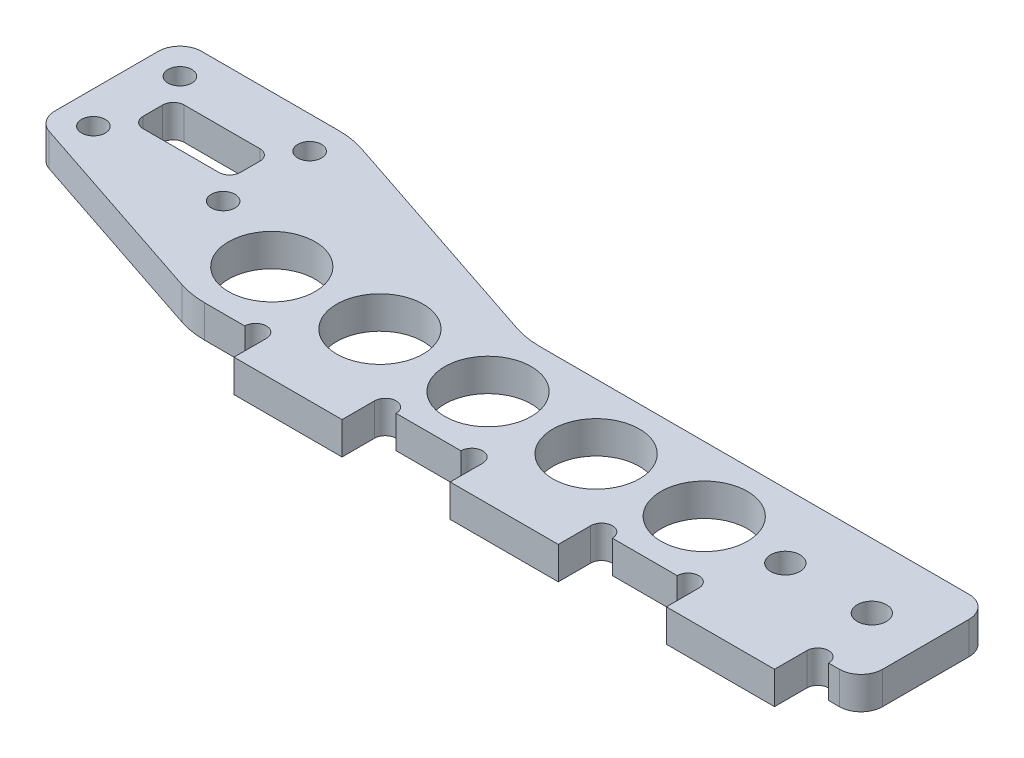
SolidWorks part; units mm, degrees
material "Thornel Mat VMA"
ref_plane "前视基准面" through (0, 0, 0) normal (0, 0, 1) x (1, 0, 0)
ref_plane "上视基准面" through (0, 0, 0) normal (0, 1, 0) x (1, 0, 0)
ref_plane "右视基准面" through (0, 0, 0) normal (1, 0, 0) x (0, 0, -1)
sketch "草图1" plane through (0, 0, 0) normal (0, 1, 0) x (1, 0, 0)
  line L1 (-41.5, -6) -> (41.5, -6)
  line L2 (-41.5, -6) -> (-41.5, 6)
  line L3 (-41.5, 6) -> (41.5, 6)
  line L4 (41.5, -6) -> (41.5, 6)
  line L5 (0, 6) -> (0, -6) construction
  line L6 (-41.5, 0) -> (41.5, 0) construction
  point P0 (0, 0)
  dimension "D4" = 83
  dimension "D5" = 12
extrude "凸台-拉伸1" add sketch "草图1" along normal blind 3
sketch "草图2" plane through (0, 3, 0) normal (0, 1, 0) x (1, 0, 0)
  line L0 (-41.5, 6) -> (-41.5, -6) construction
  line L1 (11.5, -6) -> (11.5, 6) construction
  line L2 (1.5, -6) -> (1.5, 6) construction
  line L3 (16.5, -9) -> (6.5, -9)
  line L4 (-13.5, -6) -> (-3.5, -6)
  line L5 (-13.5, -6) -> (-13.5, -9)
  line L6 (-13.5, -9) -> (-3.5, -9)
  line L7 (-3.5, -6) -> (-3.5, -9)
  line L12 (6.5, -6) -> (6.5, -9)
  line L13 (16.5, -6) -> (6.5, -6)
  line L14 (16.5, -6) -> (16.5, -9)
  line L15 (36.5, -9) -> (26.5, -9)
  line L16 (41.5, 6) -> (-41.5, 6) construction
  line L17 (-41.5, -6) -> (41.5, -6) construction
  line L18 (26.5, -6) -> (26.5, -9)
  line L19 (36.5, -6) -> (26.5, -6)
  line L20 (36.5, -6) -> (36.5, -9)
  dimension "D1" = 43
  dimension "D3" = 3
  dimension "D4" = 10
  dimension "D5" = 10
extrude "凸台-拉伸2" add sketch "草图2" against normal up to surface (3 mm away) up to face at (0, 0, 0)
sketch "草图3" plane through (0, 0, 0) normal (0, -1, 0) x (1, 0, 0)
  line L0 (16.5, 6) -> (26.5, 6) construction
  line L1 (-3.5, 6) -> (6.5, 6) construction
  line L2 (-41.5, 6) -> (-13.5, 6) construction
  line L3 (21.5, 6) -> (21.5, -6) construction
  line L4 (16.5, 6) -> (26.5, 6) construction
  line L5 (41.5, -6) -> (-41.5, -6) construction
  circle A0 centre (17.5, 6) radius 1
  circle A1 centre (5.5, 6) radius 1
  circle A2 centre (-2.5, 6) radius 1
  circle A3 centre (-14.5, 6) radius 1
  circle A4 centre (25.5, 6) radius 1
  circle A5 centre (37.5, 6) radius 1
  dimension "D1" = 2
extrude "切除-拉伸1" cut sketch "草图3" against normal through all
sketch "草图4" plane through (0, 3, 0) normal (0, 1, 0) x (1, 0, 0)
  line L0 (28.5, 3.5) -> (28.5, -3.5) construction
  line L1 (41.5, -6) -> (41.5, 6) construction
  line L2 (28.5, 0) -> (41.5, 0) construction
  circle A2 centre (28.5, 0) radius 1.35
  circle A3 centre (36.5, 0) radius 1.35
  dimension "D1" = 5
  dimension "D2" = 2.7
  dimension "D3" = 7
  dimension "D4" = 8
extrude "切除-拉伸2" cut sketch "草图4" against normal through all
sketch "草图6" plane through (0, 3, 0) normal (0, 1, 0) x (1, 0, 0)
  line L1 (-41.5, -6) -> (-15.5, -6) construction
  line L15 (-41.5, 1) -> (-20.5, -6)
  line L16 (-41.5, 6) -> (-41.5, -6) construction
  line L17 (-20.5, -6) -> (-41.5, -6)
  line L18 (-41.5, -6) -> (-41.5, 1)
  dimension "D3" = 21
  dimension "D4" = 7
extrude "切除-拉伸3" cut sketch "草图6" against normal through all
sketch "草图5" plane through (0, 3, 0) normal (0, 1, 0) x (1, 0, 0)
  line L0 (-41.5, 6) -> (-41.5, 1) construction
  line L1 (-41.5, 14) -> (-25.5, 14)
  line L8 (41.5, 6) -> (-41.5, 6) construction
  line L10 (-41.5, 14) -> (-41.5, 6)
  line L11 (-41.5, 6) -> (-1.5, 6)
  line L13 (-25.5, 14) -> (-1.5, 6)
  line L18 (-20.5, -6) -> (-41.5, 1) construction
  line L19 (-20.5, -6) -> (-15.5, -6) construction
  dimension "D1" = 20
  dimension "D2" = 16
extrude "凸台-拉伸3" add sketch "草图5" against normal blind 3
sketch "草图9" plane through (0, 3, 0) normal (0, 1, 0) x (1, 0, 0)
  line L0 (-32.5, 14) -> (-32.5, -6) construction
  line L1 (-25.5, 14) -> (-41.5, 14) construction
  line L2 (-20.5, -6) -> (-15.5, -6) construction
  line L3 (-41.5, 7) -> (-18.8512, 7) construction
  line L4 (-41.5, 14) -> (-41.5, 1) construction
  line L6 (-37, 5.1) -> (-28, 5.1)
  line L7 (-37, 5.1) -> (-37, 8.9)
  line L8 (-37, 8.9) -> (-28, 8.9)
  line L9 (-28, 5.1) -> (-28, 8.9)
  line L10 (-32.5, 8.9) -> (-32.5, 5.1) construction
  line L11 (-37, 7) -> (-28, 7) construction
  circle A0 centre (-38.5, 11) radius 1.1
  circle A1 centre (-38.5, 3) radius 1.1
  circle A2 centre (-26.5, 3) radius 1.1
  circle A3 centre (-26.5, 11) radius 1.1
  point P18 (-32.5, 7)
  dimension "D5" = 2.2
  dimension "D1" = 12
  dimension "D2" = 8
  dimension "D3" = 3
  dimension "D4" = 3
  dimension "D6" = 9
  dimension "D7" = 3.8
extrude "切除-拉伸6" cut sketch "草图9" against normal through all
sketch "草图8" plane through (0, 3, 0) normal (0, 1, 0) x (1, 0, 0)
  line L0 (-9, 0) -> (11, 0) construction
  line L5 (-41.5, 14) -> (-41.5, 1) construction
  line L6 (-13.5, -9) -> (-3.5, -9) construction
  line L7 (11, 0) -> (11, 6) construction
  line L8 (41.5, 6) -> (-1.5, 6) construction
  circle A1 centre (11, 0) radius 4
  circle A2 centre (1, 0) radius 4
  circle A3 centre (-9, 0) radius 4
  circle A4 centre (-19, 0) radius 4
  circle A5 centre (21, 0) radius 4
  dimension "D1" = 4
  dimension "D2" = 8
  dimension "D3" = 10
  dimension "D4" = 9
  dimension "D5" = 22.5
extrude "切除-拉伸5" cut sketch "草图8" against normal through all
fillet "圆角1" radius 8 3 edges at (-20.5, 1.5, 6) (-25.5, 1.5, -14) (-1.5, 1.5, -6)
fillet "圆角2" radius 2 4 edges at (41.5, 1.5, 6) (41.5, 1.5, -6) (-41.5, 1.5, -1) (-41.5, 1.5, -14)
fillet "圆角3" radius 1 4 edges at (-28, 1.5, -5.1) (-37, 1.5, -5.1) (-37, 1.5, -8.9) (-28, 1.5, -8.9)
